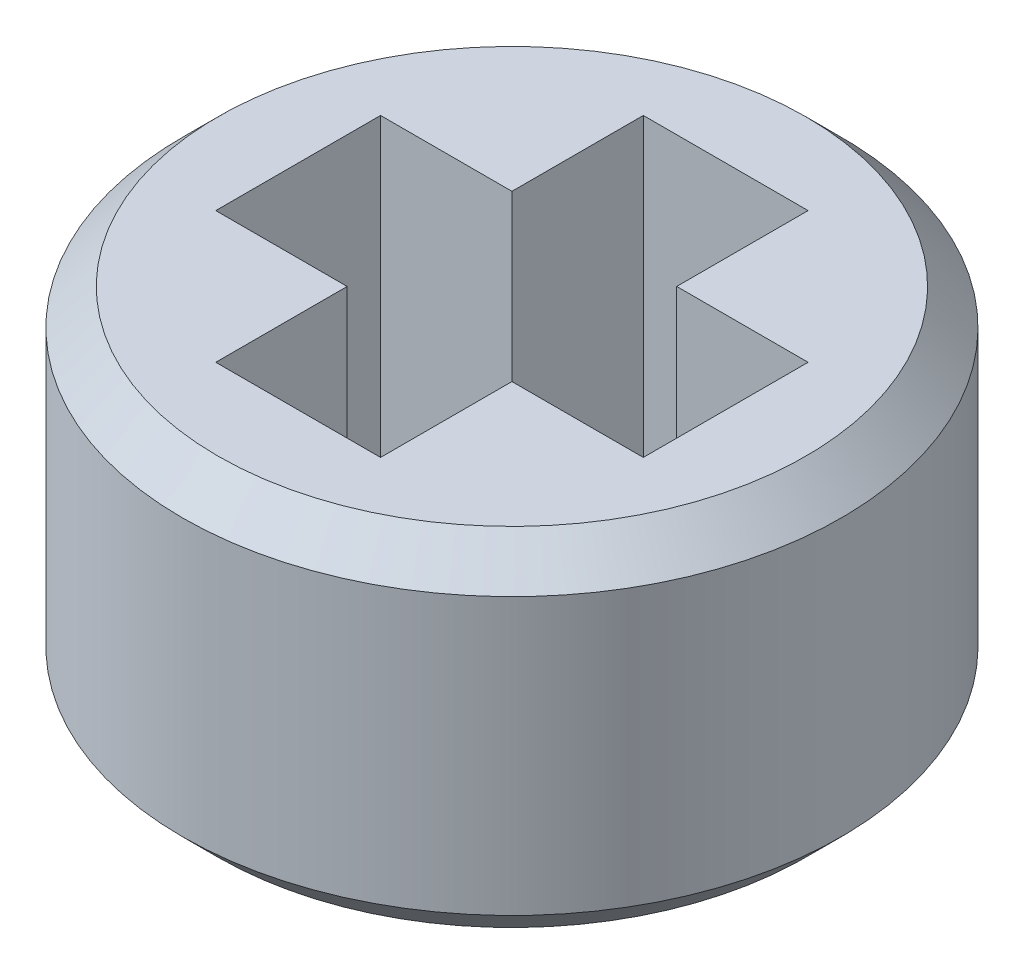
SolidWorks part; units mm, degrees
ref_plane "Front Plane" through (0, 0, 0) normal (0, 0, 1) x (1, 0, 0)
ref_plane "Top Plane" through (0, 0, 0) normal (0, 1, 0) x (1, 0, 0)
ref_plane "Right Plane" through (0, 0, 0) normal (1, 0, 0) x (0, 0, -1)
sketch "Sketch1" plane through (0, 0, 0) normal (0, 1, 0) x (1, 0, 0)
  circle A0 centre (0, 0) radius 3.7
  dimension "D1" = 7.4
extrude "Boss-Extrude1" add sketch "Sketch1" along normal mid plane 3.9
sketch "Sketch2" plane through (0, 1.95, 0) normal (0, 1, 0) x (1, 0, 0)
  line L0 (0.925, 0.925) -> (2.4, 0.925)
  line L1 (-2.4, 0.925) -> (-0.925, 0.925)
  line L2 (-2.4, 0.925) -> (-2.4, -0.925)
  line L3 (-2.4, -0.925) -> (-0.925, -0.925)
  line L4 (2.4, 0.925) -> (2.4, -0.925)
  line L5 (-2.4, 0.925) -> (2.4, -0.925) construction
  line L6 (-2.4, -0.925) -> (2.4, 0.925) construction
  line L7 (-0.925, 2.4) -> (0.925, 2.4)
  line L8 (-0.925, 2.4) -> (-0.925, 0.925)
  line L9 (-0.925, -2.4) -> (0.925, -2.4)
  line L10 (0.925, 2.4) -> (0.925, 0.925)
  line L11 (-0.925, 2.4) -> (0.925, -2.4) construction
  line L12 (-0.925, -2.4) -> (0.925, 2.4) construction
  line L13 (0.925, -0.925) -> (2.4, -0.925)
  line L14 (-0.925, -0.925) -> (-0.925, -2.4)
  line L15 (0.925, -0.925) -> (0.925, -2.4)
  point P0 (0, 0)
  point P6 (0, 0)
  dimension "D1" = 1.85
  dimension "D2" = 1.85
  dimension "D3" = 4.8
  dimension "D4" = 4.8
extrude "Cut-Extrude1" cut sketch "Sketch2" against normal through all
chamfer "Chamfer1" distance 0.4 angle 45 2 edges at (0, -1.95, 3.7) (0, 1.95, 3.7)
